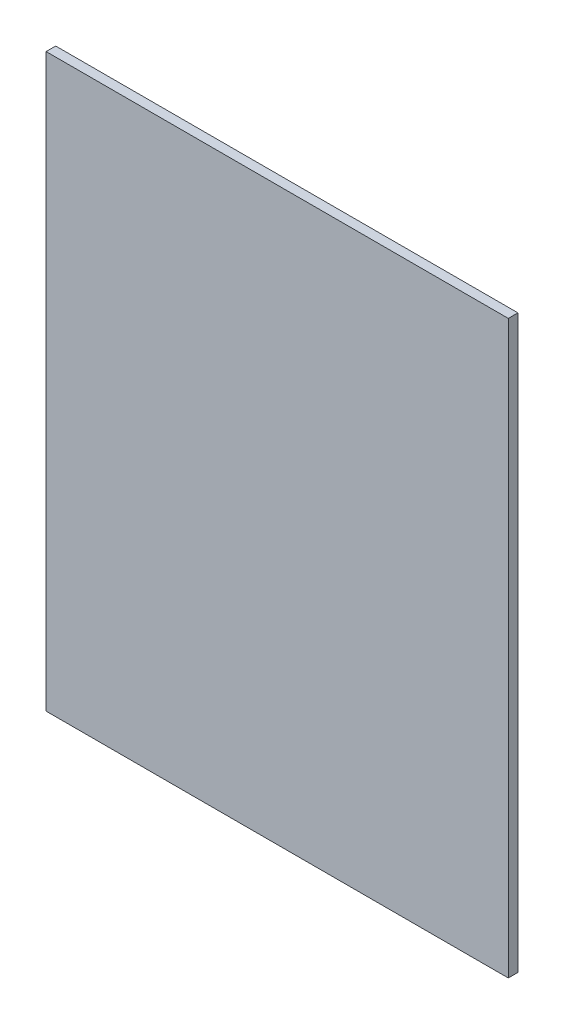
SolidWorks part; units mm, degrees
ref_plane "Front Plane" through (0, 0, 0) normal (0, 0, 1) x (1, 0, 0)
ref_plane "Top Plane" through (0, 0, 0) normal (0, 1, 0) x (1, 0, 0)
ref_plane "Right Plane" through (0, 0, 0) normal (1, 0, 0) x (0, 0, -1)
sketch "Sketch1" plane through (0, 0, 0) normal (0, 0, 1) x (1, 0, 0)
  line L1 (-438.9437, 542.5281) -> (438.9438, 542.5281)
  line L2 (-438.9437, 542.5281) -> (-438.9437, -542.5281)
  line L3 (-438.9437, -542.5281) -> (438.9438, -542.5281)
  line L4 (438.9438, 542.5281) -> (438.9438, -542.5281)
  line L5 (-438.9437, 542.5281) -> (438.9438, -542.5281) construction
  line L6 (-438.9437, -542.5281) -> (438.9438, 542.5281) construction
  point P0 (0, 0)
  dimension "D1" = 1085.0563
  dimension "D2" = 877.8875
extrude "Boss-Extrude1" add sketch "Sketch1" along normal blind 18.2562
